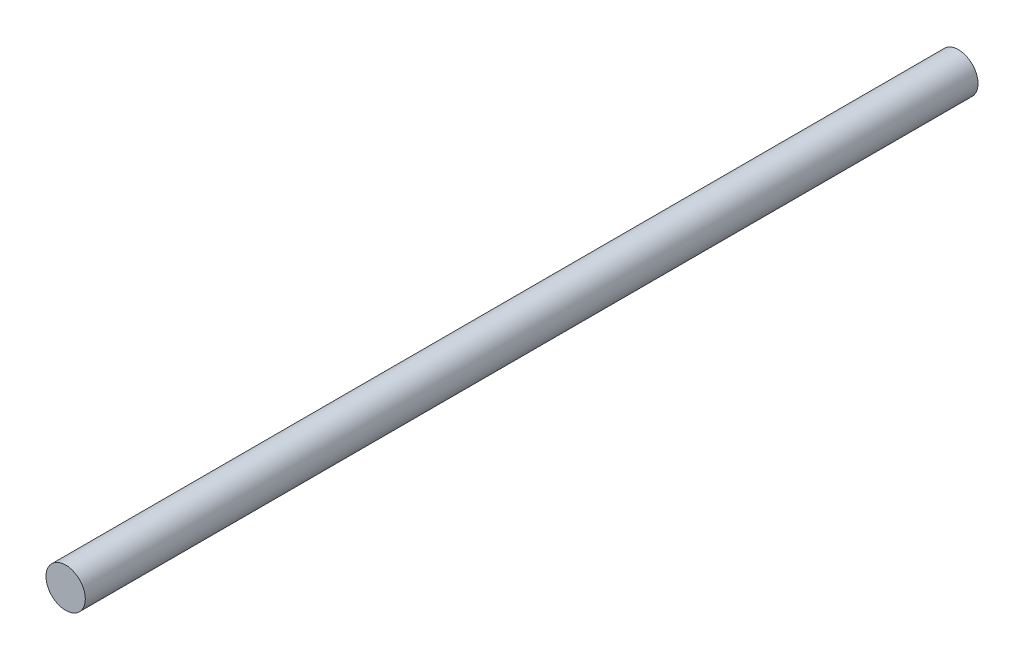
SolidWorks part; units mm, degrees
ref_plane "前视基准面" through (0, 0, 0) normal (0, 0, 1) x (1, 0, 0)
ref_plane "上视基准面" through (0, 0, 0) normal (0, 1, 0) x (1, 0, 0)
ref_plane "右视基准面" through (0, 0, 0) normal (1, 0, 0) x (0, 0, -1)
other "Configuration Table"
sketch "草图1" plane through (0, 0, 0) normal (0, 0, 1) x (1, 0, 0)
  circle A0 centre (0, 0) radius 0.7
extrude "凸台-拉伸1" add sketch "草图1" along normal blind 35
sketch "草图2" plane through (0, 0, 0) normal (0, 0, -1) x (-1, 0, 0)
  circle A0 centre (0, 0) radius 1.415
extrude "切除-拉伸2" cut sketch "草图2" against normal blind 3.2
